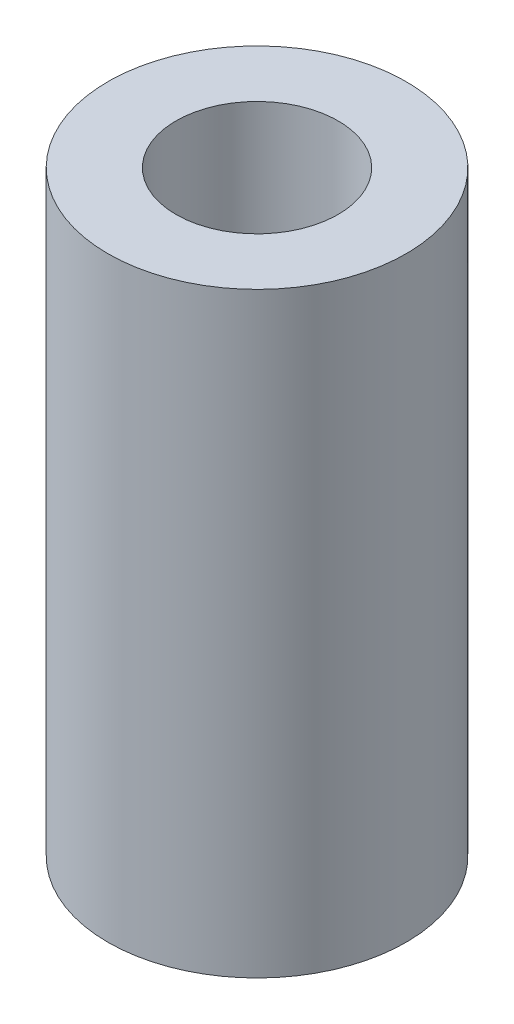
SolidWorks part; units mm, degrees
ref_plane "Front Plane" through (0, 0, 0) normal (0, 0, 1) x (1, 0, 0)
ref_plane "Top Plane" through (0, 0, 0) normal (0, 1, 0) x (1, 0, 0)
ref_plane "Right Plane" through (0, 0, 0) normal (1, 0, 0) x (0, 0, -1)
sketch "Sketch1" plane through (0, 0, 0) normal (0, 1, 0) x (1, 0, 0)
  circle A0 centre (0, 0) radius 3.175
  dimension "D1" = 6.35
extrude "Boss-Extrude1" add sketch "Sketch1" along normal blind 12.7
sketch "Sketch2" plane through (0, 12.7, 0) normal (0, 1, 0) x (1, 0, 0)
  circle A0 centre (0, 0) radius 1.7272
  dimension "D1" = 3.4544
extrude "Cut-Extrude1" cut sketch "Sketch2" against normal blind 3.9688 and the other way through all
ref_plane "Plane1" through (0, 6.35, 0) normal (0, 1, 0) x (1, 0, 0)
mirror "Mirror1" about plane through (0, 6.35, 0) normal (0, 1, 0) of "Cut-Extrude1"
